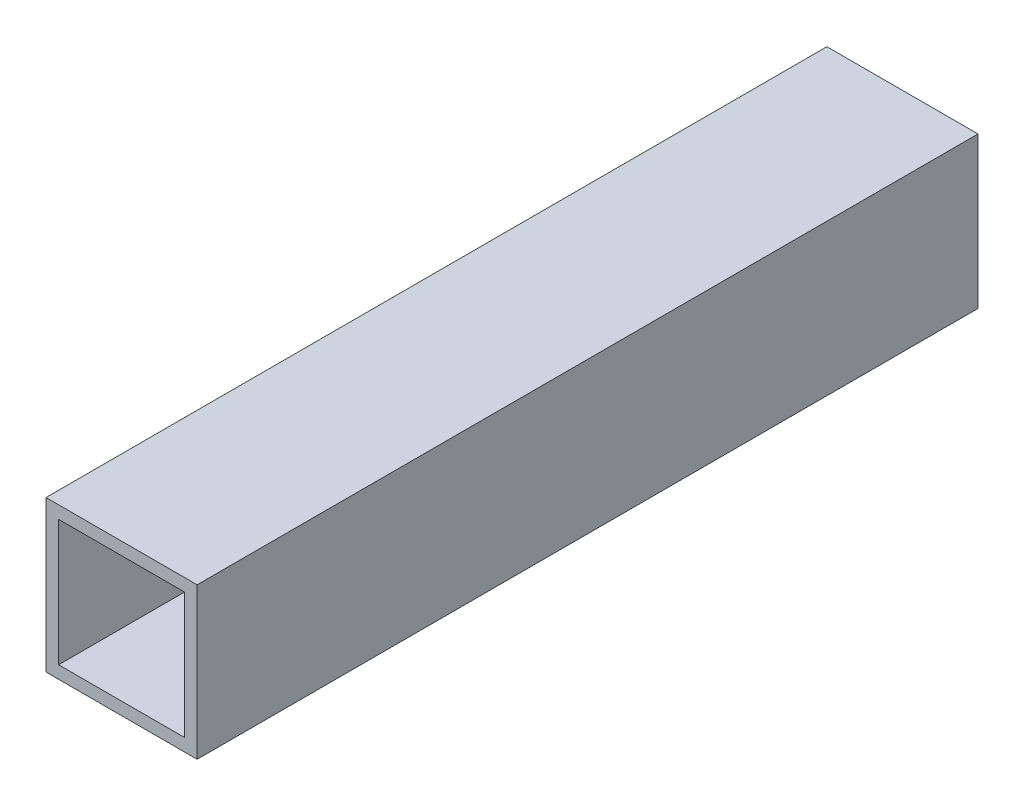
SolidWorks part; units mm, degrees
ref_plane "前视基准面" through (0, 0, 0) normal (0, 0, 1) x (1, 0, 0)
ref_plane "上视基准面" through (0, 0, 0) normal (0, 1, 0) x (1, 0, 0)
ref_plane "右视基准面" through (0, 0, 0) normal (1, 0, 0) x (0, 0, -1)
sketch "草图1" plane through (0, 0, 0) normal (0, 0, 1) x (1, 0, 0)
  line L0 (-12, 12) -> (12, 12)
  line L1 (-10, 10) -> (10, 10)
  line L2 (-10, 10) -> (-10, -10)
  line L3 (-10, -10) -> (10, -10)
  line L4 (10, 10) -> (10, -10)
  line L5 (-10, 10) -> (10, -10) construction
  line L6 (-10, -10) -> (10, 10) construction
  line L7 (12, 12) -> (12, -12)
  line L8 (-12, -12) -> (12, -12)
  line L9 (-12, 12) -> (-12, -12)
  point P0 (0, 0)
  dimension "D1" = 20
  dimension "D2" = 20
  dimension "D3" = 2
extrude "凸台-拉伸1" add sketch "草图1" along normal mid plane 124
